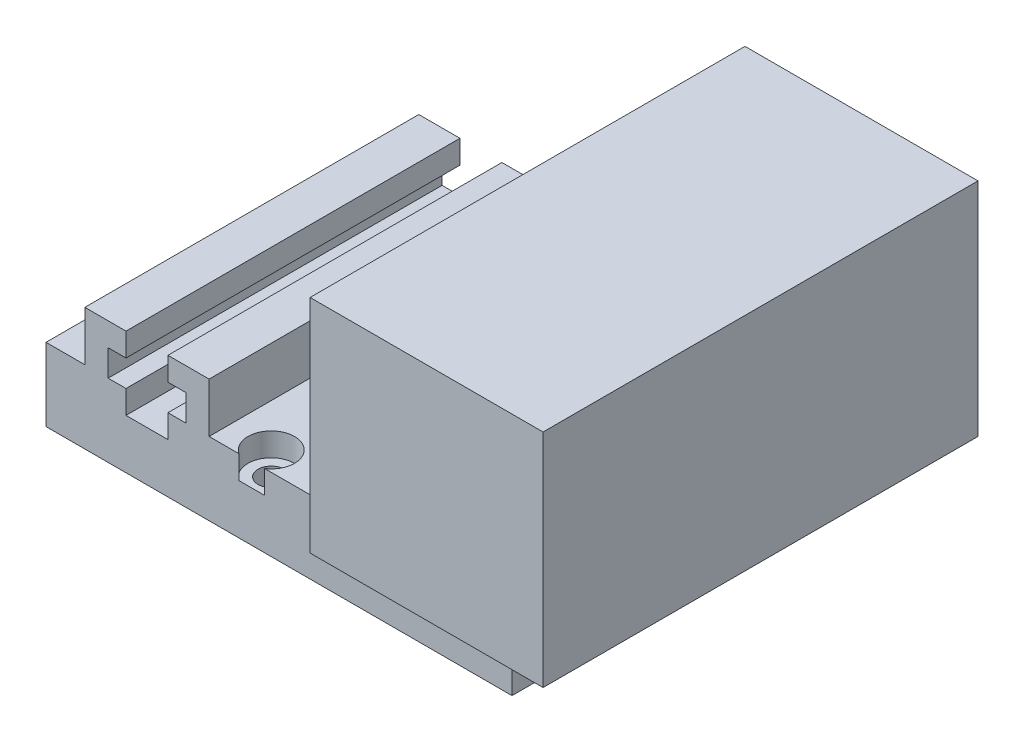
SolidWorks part; units mm, degrees
ref_plane "Front Plane" through (0, 0, 0) normal (0, 0, 1) x (1, 0, 0)
ref_plane "Top Plane" through (0, 0, 0) normal (0, 1, 0) x (1, 0, 0)
ref_plane "Right Plane" through (0, 0, 0) normal (1, 0, 0) x (0, 0, -1)
sketch "Sketch1" plane through (0, 0, 0) normal (0, 1, 0) x (1, 0, 0)
  line L1 (0, 0) -> (60, 0)
  line L2 (0, 0) -> (0, 43)
  line L3 (0, 43) -> (60, 43)
  line L4 (60, 0) -> (60, 43)
  dimension "D1" = 60
  dimension "D2" = 43
extrude "Boss-Extrude1" add sketch "Sketch1" along normal blind 5
sketch "Sketch2" plane through (0, 0, 0) normal (0, -1, 0) x (-1, 0, 0)
  line L0 (-60, 0) -> (-60, 43) construction
  line L1 (0, 0) -> (-60, 0)
  line L2 (0, 0) -> (0, 5)
  line L3 (0, 5) -> (-60, 5)
  line L4 (-60, 0) -> (-60, 5)
  line L6 (0, 43) -> (0, 0) construction
  line L7 (0, 43) -> (-60, 43)
  line L8 (0, 43) -> (0, 38)
  line L9 (0, 38) -> (-60, 38)
  line L10 (-60, 43) -> (-60, 38)
  point P11 (0, 21.5)
  dimension "D1" = 5
extrude "Boss-Extrude2" add sketch "Sketch2" along normal blind 4.4
sketch "Sketch3" plane through (0, 5, 0) normal (0, 1, 0) x (1, 0, 0)
  line L0 (60, 43) -> (0, 43) construction
  line L1 (5, 43) -> (8, 43)
  line L2 (5, 43) -> (5, 0)
  line L3 (5, 0) -> (8, 0)
  line L4 (8, 43) -> (8, 0)
  line L5 (0, 0) -> (60, 0) construction
  line L6 (0, 43) -> (0, 0) construction
  line L7 (18, 43) -> (21, 43)
  line L8 (18, 43) -> (18, 0)
  line L9 (18, 0) -> (21, 0)
  line L10 (21, 43) -> (21, 0)
  dimension "D1" = 3
  dimension "D2" = 10
  dimension "D3" = 5
extrude "Boss-Extrude3" add sketch "Sketch3" along normal blind 6.4
sketch "Sketch4" plane through (8, 0, 0) normal (1, 0, 0) x (0, 0, -1)
  line L0 (43, 11.4) -> (43, 5) construction
  line L1 (0, 11.4) -> (43, 11.4)
  line L2 (0, 11.4) -> (0, 8.4)
  line L3 (0, 8.4) -> (43, 8.4)
  line L4 (43, 11.4) -> (43, 8.4)
  dimension "D1" = 3
extrude "Boss-Extrude4" add sketch "Sketch4" along normal blind 2.3
ref_plane "Plane1" through (13, 0, 0) normal (1, 0, 0) x (0, 0, -1)
mirror "Mirror1" about plane through (13, 0, 0) normal (1, 0, 0) of "Boss-Extrude4"
sketch "Sketch5" plane through (0, 5, 0) normal (0, 1, 0) x (1, 0, 0)
  line L1 (40.5, 49.5) -> (70.5, 49.5)
  line L2 (40.5, 49.5) -> (40.5, -6.5)
  line L3 (40.5, -6.5) -> (70.5, -6.5)
  line L4 (70.5, 49.5) -> (70.5, -6.5)
  line L6 (13, -1.87) -> (13, 1.87) construction
  line L7 (60, 0) -> (60, 43) construction
  line L8 (60, 21.5) -> (70.5, 21.5) construction
  dimension "D1" = 30
  dimension "D2" = 27.5
  dimension "D3" = 56
extrude "Boss-Extrude5" add sketch "Sketch5" along normal blind 28.5
sketch "Sketch6" plane through (40.5, 0, 0) normal (-1, 0, 0) x (0, 0, 1)
  line L0 (-43, 5) -> (0, 5) construction
  line L1 (-41.7, 30.7) -> (-1.3, 30.7)
  line L2 (-41.7, 30.7) -> (-41.7, 10.3)
  line L3 (-41.7, 10.3) -> (-1.3, 10.3)
  line L4 (-1.3, 30.7) -> (-1.3, 10.3)
  line L5 (-49.5, 33.5) -> (6.5, 33.5) construction
  line L6 (-21.5, 30.7) -> (-21.5, 33.5) construction
  point P4 (-41.7, 20.5)
  point P10 (-21.5, 30.7)
  dimension "D1" = 20.4
  dimension "D2" = 15.5
  dimension "D3" = 40.4
extrude "Cut-Extrude1" cut sketch "Sketch6" against normal blind 28
sketch "Sketch7" plane through (40.5, 0, 0) normal (-1, 0, 0) x (0, 0, 1)
  line L0 (-46, 25.5) -> (3, 25.5) construction
  line L1 (-49.5, 33.5) -> (6.5, 33.5) construction
  line L2 (-21.5, 25.5) -> (-21.5, 33.5) construction
  line L3 (3, 25.5) -> (3, 15.5)
  line L4 (3, 20.5) -> (-1.3, 20.5) construction
  line L5 (-1.3, 10.3) -> (-1.3, 30.7) construction
  circle A0 centre (-46, 25.5) radius 1.05
  circle A1 centre (-46, 15.5) radius 1.05
  circle A2 centre (3, 25.5) radius 1.05
  circle A3 centre (3, 15.5) radius 1.05
  point P16 (0, 0)
  dimension "D1" = 2.1
  dimension "D2" = 10
  dimension "D3" = 49
extrude "Cut-Extrude2" cut sketch "Sketch7" against normal blind 25
sketch "Sketch8" plane through (0, 0, 0) normal (0, 0, 1) x (1, 0, 0)
  line L0 (8, 5) -> (18, 5) construction
  line L1 (10.3, 5) -> (15.7, 5)
  line L2 (10.3, 5) -> (10.3, 2)
  line L3 (10.3, 2) -> (15.7, 2)
  line L4 (15.7, 5) -> (15.7, 2)
  line L5 (13, -1.87) -> (13, 1.87) construction
  point P6 (13, 5)
  dimension "D1" = 3
  dimension "D2" = 5.4
extrude "Cut-Extrude3" cut sketch "Sketch8" against normal up to next
sketch "Sketch9" plane through (0, 5, 0) normal (0, 1, 0) x (1, 0, 0)
  line L0 (40.5, 43) -> (21, 43) construction
  line L1 (40.5, 49.5) -> (40.5, -6.5) construction
  line L2 (0, 21.5) -> (50000, 21.5) construction
  line L3 (0, 43) -> (0, 0) construction
  circle A0 centre (26.5, 40.5) radius 1.7
  circle A1 centre (36.5, 40.5) radius 1.7
  circle A2 centre (36.5, 2.5) radius 1.7
  circle A3 centre (26.5, 2.5) radius 1.7
  point P12 (0, 21.5)
  point P13 (26.6203, 32.317)
  point P14 (0, 0)
  dimension "D1" = 3.4
  dimension "D2" = 10
  dimension "D3" = 2.5
  dimension "D4" = 4
extrude "Cut-Extrude4" cut sketch "Sketch9" against normal up to next
sketch "Sketch10" plane through (0, 5, 0) normal (0, 1, 0) x (1, 0, 0)
  circle A0 centre (26.5, 40.5) radius 3
  circle A1 centre (36.5, 40.5) radius 3
  circle A2 centre (26.5, 2.5) radius 3
  circle A3 centre (36.5, 2.5) radius 3
  dimension "D1" = 6
extrude "Cut-Extrude5" cut sketch "Sketch10" against normal blind 3
